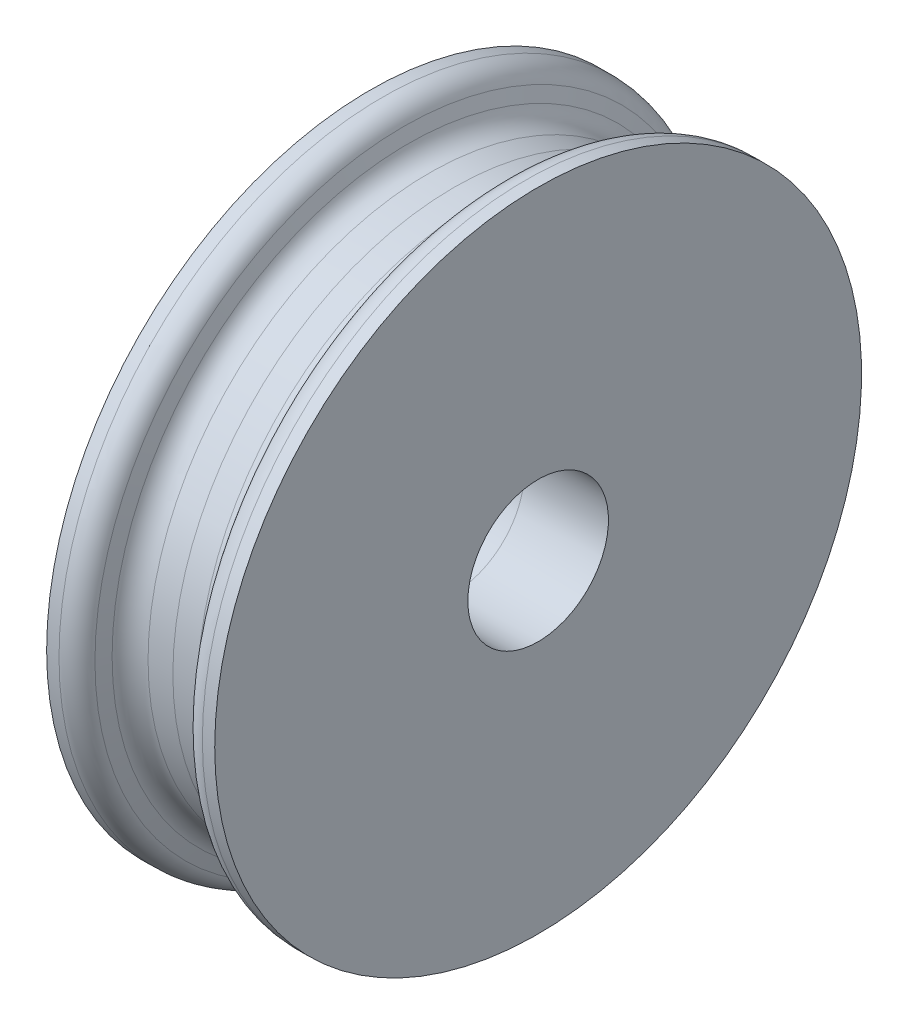
SolidWorks part; units mm, degrees
ref_plane "Front" through (0, 0, 0) normal (0, 0, 1) x (1, 0, 0)
ref_plane "Top" through (0, 0, 0) normal (0, 1, 0) x (1, 0, 0)
ref_plane "Right" through (0, 0, 0) normal (1, 0, 0) x (0, 0, -1)
ref_plane "Plane1" through (25.3264, 0, 0) normal (-1, 0, 0) x (0, 0, 1)
sketch "Sketch2" plane through (0, 0, 0) normal (0, 0, 1) x (1, 0, 0)
  line L0 (3.175, 7.9375) -> (22.1514, 7.9375)
  line L2 (22.1514, 36.5125) -> (18.9764, 36.5125)
  line L3 (18.9764, 36.5125) -> (17.243, 31.75)
  line L4 (17.243, 31.75) -> (8.0834, 31.75)
  line L5 (8.0834, 31.75) -> (6.35, 36.5125)
  line L6 (6.35, 36.5125) -> (3.175, 36.5125)
  line L8 (-22.1514, 0) -> (22.1514, 0) construction
  line L9 (12.6632, 31.75) -> (12.6632, -1.8762) construction
  line L11 (3.175, 7.9375) -> (3.175, 36.5125)
  line L13 (22.1514, 7.9375) -> (22.1514, 36.5125)
  line L15 (25.3264, 8.999) -> (25.3264, -8.999) construction
  point P0 (0, 0)
  point P2 (11.3175, 13.4699)
  point P5 (12.6632, 7.9375)
  point P14 (0, 0)
  point P17 (2.6609, 15.7949)
  point P18 (-7.2323, 22.1265)
  point P19 (0, 0)
  point P20 (0, 0)
  point P22 (0, 0)
  point P23 (0, 0)
  point P24 (0, 0)
  point P25 (0, 0)
  point P26 (26.2419, 7.9375)
  point P27 (0, 0)
  point P28 (0, 0)
  dimension "D1" = 15.875
  dimension "D2" = 73.025
  dimension "D3" = 3.175
  dimension "D4" = 3.175
  dimension "D5" = 70
  dimension "D6" = 4.7625
  dimension "D7" = 3.175
revolve "Revolve1" add sketch "Sketch2" angle 360 about L8
fillet "Fillet1" radius 2.54 4 edges at (6.35, 0, 36.5125) (18.9764, 0, 36.5125) (17.243, 0, 31.75) (8.0834, 0, 31.75)
ref_plane "Plane2" through (12.6632, 0, 0) normal (1, 0, 0) x (0, 0, -1)
split "Split1" trim tools "Plane2" bodies to split 101 resulting bodies 102 103
